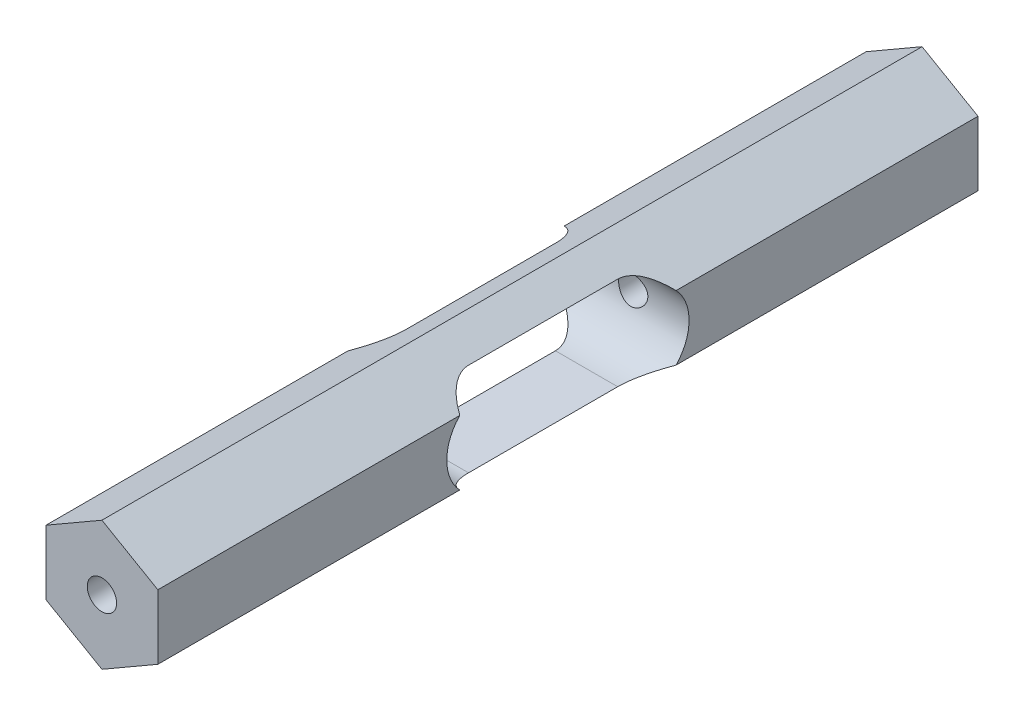
SolidWorks part; units mm, degrees
material "6061-T6 (SS)"
ref_plane "Front Plane" through (0, 0, 0) normal (0, 0, 1) x (1, 0, 0)
ref_plane "Top Plane" through (0, 0, 0) normal (0, 1, 0) x (1, 0, 0)
ref_plane "Right Plane" through (0, 0, 0) normal (1, 0, 0) x (0, 0, -1)
sketch "Sketch1" plane through (0, 0, 0) normal (0, 0, 1) x (1, 0, 0)
  line L1 (0, 5.4993) -> (-4.7625, 2.7496)
  line L2 (-4.7625, 2.7496) -> (-4.7625, -2.7496)
  line L3 (-4.7625, -2.7496) -> (0, -5.4993)
  line L4 (0, -5.4993) -> (4.7625, -2.7496)
  line L5 (4.7625, -2.7496) -> (4.7625, 2.7496)
  line L6 (4.7625, 2.7496) -> (0, 5.4993)
  circle A1 centre (0, 0) radius 4.7625 construction
  dimension "D1" = 9.525
extrude "Boss-Extrude1" add sketch "Sketch1" along normal mid plane 69.85
sketch "Sketch5" plane through (0, 0, 0) normal (1, 0, 0) x (0, 0, -1)
  line L0 (-6.35, 0) -> (6.35, 0) construction
  line L1 (-6.35, 3.9688) -> (6.35, 3.9688)
  line L2 (-6.35, -3.9687) -> (6.35, -3.9687)
  arc A0 (-6.35, 3.9688) -> (-6.35, -3.9687) centre (-6.35, 0) ccw
  arc A1 (6.35, -3.9687) -> (6.35, 3.9688) centre (6.35, 0) ccw
  point P3 (0, 0)
  dimension "D1" = 7.9375
  dimension "D2" = 12.7
extrude "Cut-Extrude4" cut sketch "Sketch5" against normal through all both and the other way through all
sketch "Sketch6" plane through (0, 0, 0) normal (0, 0, 1) x (1, 0, 0)
  circle A0 centre (0, 0) radius 1.25
  dimension "D1" = 2.5
extrude "Cut-Extrude5" cut sketch "Sketch6" against normal through all both and the other way through all
